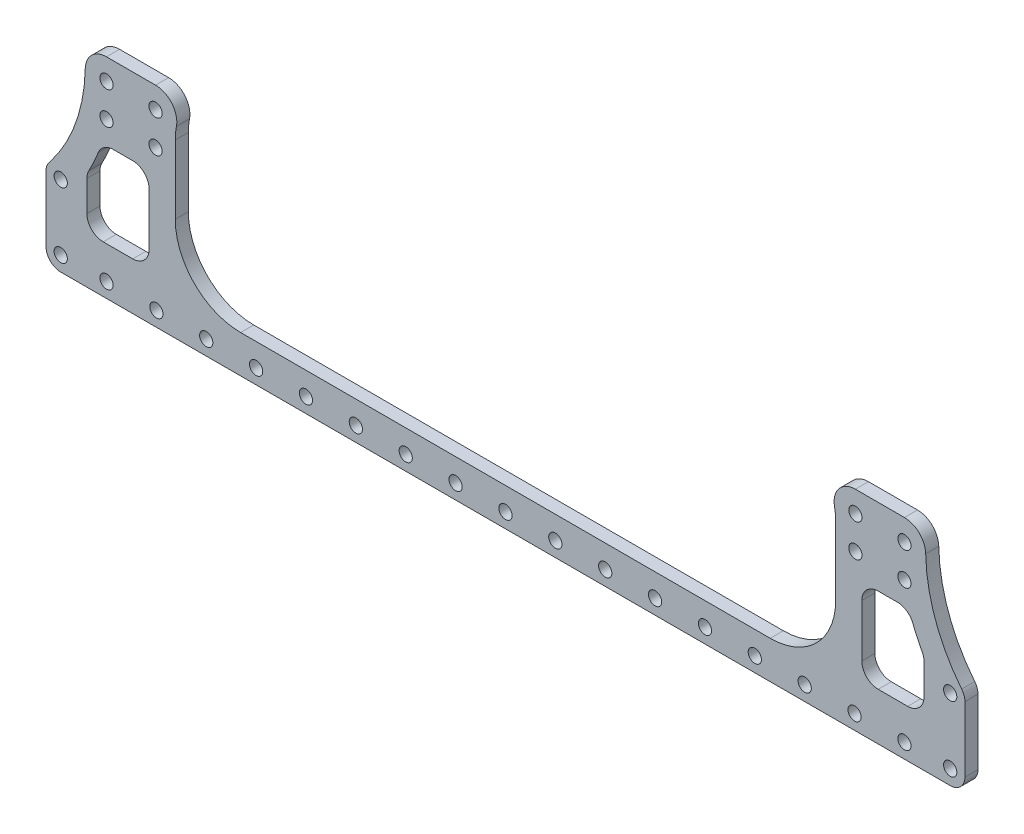
SolidWorks part; units mm, degrees
material "Thornel Mat VMA"
ref_plane "前视基准面" through (0, 0, 0) normal (0, 0, 1) x (1, 0, 0)
ref_plane "上视基准面" through (0, 0, 0) normal (0, 1, 0) x (1, 0, 0)
ref_plane "右视基准面" through (0, 0, 0) normal (1, 0, 0) x (0, 0, -1)
other "Configuration Table"
sketch "草图1" plane through (0, 0, 0) normal (0, 0, 1) x (1, 0, 0)
  line L0 (0, 0) -> (17960.6475, 0) construction
  line L1 (-122, -5) -> (-122, -28) construction
  line L2 (-107, -5) -> (-122, -5) construction
  line L3 (-107, -5) -> (-107, 5) construction
  line L4 (-107, 5) -> (-122, 5) construction
  line L5 (-122, -5) -> (-122, 5) construction
  line L6 (-107, -5) -> (-122, 5) construction
  line L7 (-107, 5) -> (-122, -5) construction
  line L8 (0, 0) -> (0, -50000) construction
  line L9 (107, 5) -> (122, -5) construction
  line L10 (-126, -9) -> (-103, -9) construction
  line L11 (-126, -9) -> (-126, 9) construction
  line L12 (-126, 9) -> (-103, 9) construction
  line L13 (-103, -9) -> (-103, 9) construction
  line L14 (-126, -9) -> (-103, 9) construction
  line L15 (-126, 9) -> (-103, -9) construction
  line L16 (-122, -28) -> (-136, -28) construction
  line L17 (126, -9) -> (103, -9) construction
  line L18 (126, -9) -> (126, 9) construction
  line L19 (126, 9) -> (103, 9) construction
  line L20 (103, -9) -> (103, 9) construction
  line L21 (126, -9) -> (103, 9) construction
  line L22 (126, 9) -> (103, -9) construction
  line L23 (-136, -32.5) -> (136, -32.5)
  line L24 (-80.976, -20) -> (80.976, -20)
  line L25 (122, -28) -> (136, -28) construction
  line L26 (126, 9) -> (103, -9) construction
  line L27 (126, -9) -> (103, 9) construction
  line L28 (103, -9) -> (103, 9) construction
  line L29 (126, 9) -> (103, 9) construction
  line L30 (126, -9) -> (126, 9) construction
  line L31 (126, -9) -> (103, -9) construction
  line L32 (107, 5) -> (122, -5) construction
  line L33 (107, -5) -> (122, 5) construction
  line L34 (122, -5) -> (122, 5) construction
  line L35 (107, 5) -> (122, 5) construction
  line L36 (107, -5) -> (107, 5) construction
  line L37 (107, -5) -> (122, -5) construction
  line L38 (122, -5) -> (122, -28) construction
  line L39 (0, 0) -> (-17960.6475, 0) construction
  line L40 (-122, 11.5) -> (-107, 11.5)
  line L41 (107, 11.5) -> (122, 11.5)
  circle A0 centre (-122, 5) radius 2.025
  circle A1 centre (-107, 5) radius 2.025
  circle A2 centre (-122, -5) radius 2.025
  circle A3 centre (-107, -5) radius 2.025
  circle A4 centre (-122, -28) radius 2.025
  circle A5 centre (122, -5) radius 2.025
  circle A6 centre (107, -5) radius 2.025
  circle A7 centre (107, 5) radius 2.025
  circle A8 centre (122, 5) radius 2.025
  circle A9 centre (-178.4887, 6.1316) radius 50
  circle A10 centre (-122, 5) radius 6.5
  circle A11 centre (-122, -28) radius 6.5 construction
  circle A12 centre (-122, -28) radius 4.5
  circle A13 centre (-136, -28) radius 2.025
  circle A14 centre (-136, -28) radius 4.5
  circle A15 centre (-107, 5) radius 6.5
  circle A17 centre (-80.976, 0) radius 20
  circle A24 centre (122, -28) radius 6.5 construction
  circle A30 centre (80.976, 0) radius 20
  circle A31 centre (107, 5) radius 6.5
  circle A32 centre (136, -28) radius 4.5
  circle A33 centre (136, -28) radius 2.025
  circle A34 centre (122, -28) radius 4.5
  circle A35 centre (122, 5) radius 6.5
  circle A36 centre (178.4887, 6.1316) radius 50
  circle A37 centre (122, -28) radius 2.025
  circle A38 centre (107, -5) radius 2.025
  circle A39 centre (122, -5) radius 2.025
  circle A40 centre (107, 5) radius 2.025
  circle A41 centre (122, 5) radius 2.025
  circle A43 centre (-106.75, -28) radius 2.025
  circle A44 centre (-91.5, -28) radius 2.025
  circle A45 centre (-76.25, -28) radius 2.025
  circle A46 centre (-61, -28) radius 2.025
  circle A47 centre (-45.75, -28) radius 2.025
  circle A48 centre (-30.5, -28) radius 2.025
  circle A49 centre (-15.25, -28) radius 2.025
  circle A50 centre (0, -28) radius 2.025
  circle A52 centre (-106.75, -28) radius 6.5 construction
  circle A53 centre (15.25, -28) radius 2.025 [skipped]
  circle A54 centre (106.75, -28) radius 2.025
  circle A55 centre (91.5, -28) radius 2.025
  circle A56 centre (76.25, -28) radius 2.025
  circle A57 centre (61, -28) radius 2.025
  circle A58 centre (45.75, -28) radius 2.025
  circle A59 centre (30.5, -28) radius 2.025
  circle A60 centre (15.25, -28) radius 2.025
  point P3 (-114.5, 0)
  point P24 (-114.5, 0)
  point P29 (114.5, 0)
  point P91 (0, -20)
  point P92 (0, -32.5)
  dimension "D3" = 4.05
  dimension "D5" = 4.05
  dimension "D8" = 4
  dimension "D9" = 13
  dimension "D10" = 100
  dimension "D11" = 13
  dimension "D12" = 9
  dimension "D14" = 40
  dimension "D1" = 10
  dimension "D2" = 15
  dimension "D4" = 122
  dimension "D6" = 23
  dimension "D7" = 4
  dimension "D13" = 14
  dimension "D15" = 10
extrude "凸台-拉伸1" add sketch "草图1" along normal blind 4
sketch "草图2" plane through (0, 0, 4) normal (0, 0, 1) x (1, 0, 0)
  circle A0 centre (-136, -28) radius 6.5 construction
  dimension "D1" = 13
sketch "草图3" plane through (0, 0, 4) normal (0, 0, 1) x (1, 0, 0)
  line L0 (140.5, -28) -> (140.5, -48)
  line L1 (136, -52.5) -> (-136, -52.5)
  line L2 (-140.5, -48) -> (-140.5, -28)
  line L3 (-136, -32.5) -> (136, -32.5) construction
  line L4 (0, -14.5949) -> (0, 23.9841) construction
  line L5 (-136, -32.5) -> (136, -32.5)
  arc A0 (136, -32.5) -> (139.5082, -25.1818) centre (136, -28) ccw construction
  arc A1 (-139.5082, -25.1818) -> (-136, -32.5) centre (-136, -28) ccw construction
  circle A2 centre (-136, -48) radius 2.025
  circle A3 centre (-136, -28) radius 2.025 construction
  circle A4 centre (-136, -48) radius 4.5
  circle A5 centre (0, -48) radius 2.025
  circle A6 centre (0, -28) radius 2.025 construction
  circle A7 centre (-15.25, -48) radius 2.025
  circle A8 centre (-30.5, -48) radius 2.025
  circle A9 centre (-45.75, -48) radius 2.025
  circle A10 centre (-61, -48) radius 2.025
  circle A11 centre (-76.25, -48) radius 2.025
  circle A12 centre (-91.5, -48) radius 2.025
  circle A13 centre (-106.75, -48) radius 2.025
  circle A14 centre (-122, -48) radius 2.025
  circle A15 centre (-15.25, -28) radius 2.025 construction
  circle A16 centre (-15.25, -28) radius 2.025 construction
  circle A18 centre (122, -48) radius 2.025
  circle A19 centre (106.75, -48) radius 2.025
  circle A20 centre (91.5, -48) radius 2.025
  circle A21 centre (76.25, -48) radius 2.025
  circle A22 centre (61, -48) radius 2.025
  circle A23 centre (45.75, -48) radius 2.025
  circle A24 centre (30.5, -48) radius 2.025
  circle A25 centre (15.25, -48) radius 2.025
  circle A26 centre (136, -48) radius 4.5
  circle A27 centre (136, -48) radius 2.025
  arc A28 (136, -32.5) -> (140.5, -28) centre (136, -28) ccw
  arc A29 (-140.5, -28) -> (-136, -32.5) centre (-136, -28) ccw
  arc M20 (-139.5082, -25.1818) -> (-136, -32.5) centre (-136, -28) ccw
  line M21 (-136, -32.5) -> (136, -32.5)
  arc M22 (136, -32.5) -> (139.5082, -25.1818) centre (136, -28) ccw
  dimension "D1" = 20
  dimension "D2" = 20
  dimension "D3" = 9
extrude "凸台-拉伸2" add sketch "草图3" against normal blind 4 contours L1 A26 L0 L2 A4 A25 A23 A21 A19 A5 A7 A8 A9 A10 A11 A12 A13 A14 A18 A20 A22 A24 M22 M21 M20 | A4 A2 | A26 A27
sketch "草图4" plane through (0, 0, 4) normal (0, 0, 1) x (1, 0, 0)
  line L0 (-100.976, 0) -> (-100.976, -41)
  line L1 (-100.976, -41) -> (100.976, -41)
  line L2 (100.976, -41) -> (100.976, 0)
  line L3 (-80.976, -20) -> (80.976, -20) construction
  line L4 (-80.976, -20) -> (80.976, -20)
  line L5 (0, -9.9748) -> (0, 31.8248) construction
  arc A0 (-100.6167, 3.7736) -> (-80.976, -20) centre (-80.976, 0) ccw construction
  arc A1 (80.976, -20) -> (100.6167, 3.7736) centre (80.976, 0) ccw construction
  arc A2 (-100.976, 0) -> (-80.976, -20) centre (-80.976, 0) ccw
  arc A3 (80.976, -20) -> (100.976, 0) centre (80.976, 0) ccw
  circle A5 centre (76.25, -48) radius 2.025 construction
  circle A6 centre (80.976, -21) radius 20
  circle A7 centre (-80.976, -21) radius 20
  dimension "D1" = 7
extrude "切除-拉伸1" cut sketch "草图4" against normal blind 4 contours A6 A3 L4 | L4 A7 L1 A6 | A7 L4 A2 | L0 A7 A2 | A6 L2 A3
sketch "草图5" plane through (0, 0, 4) normal (0, 0, 1) x (1, 0, 0)
  circle A0 centre (106.75, -28) radius 2.025 construction
  circle A1 centre (122, -28) radius 2.025 construction
  circle A2 centre (-122, -28) radius 2.025 construction
  circle A3 centre (-106.75, -28) radius 2.025 construction
  circle A4 centre (106.75, -28) radius 2.025
  circle A5 centre (122, -28) radius 2.025
  circle A6 centre (-122, -28) radius 2.025
  circle A7 centre (-106.75, -28) radius 2.025
extrude "凸台-拉伸3" add sketch "草图5" against normal blind 4
sketch "草图6" plane through (0, 0, 4) normal (0, 0, 1) x (1, 0, 0)
  line L0 (-108.976, -12) -> (-123.3956, -12)
  line L1 (-108.976, -12) -> (-108.976, -38)
  line L2 (-108.976, -38) -> (-128, -38)
  line L3 (-128, -38) -> (-128, -22.4148)
  line L4 (-100.976, 0) -> (-100.976, -21) construction
  line L5 (0, -16.786) -> (0, 30.4801) construction
  line L6 (128, -38) -> (128, -22.4148)
  line L7 (108.976, -38) -> (128, -38)
  line L8 (108.976, -12) -> (108.976, -38)
  line L9 (108.976, -12) -> (123.3956, -12)
  arc A0 (-128, -22.4148) -> (-123.3956, -12) centre (-178.4887, 6.1316) ccw
  arc A1 (-139.5082, -25.1818) -> (-128.4987, 5.1302) centre (-178.4887, 6.1316) ccw construction
  circle A2 centre (-107, -5) radius 2.025 construction
  circle A3 centre (-106.75, -48) radius 2.025 construction
  circle A4 centre (-136, -28) radius 2.025 construction
  arc A5 (128, -22.4148) -> (123.3956, -12) centre (178.4887, 6.1316) cw
  dimension "D1" = 8
  dimension "D2" = 7
  dimension "D3" = 10
  dimension "D4" = 8
  dimension "D5" = 8
extrude "切除-拉伸2" cut sketch "草图6" against normal blind 4
fillet "圆角1" radius 5 10 edges at (128, -38, 2) (123.3956, -12, 2) (128, -22.4148, 2) (-128, -38, 2) (-128, -22.4148, 2) (-123.3956, -12, 2) (-108.976, -12, 2) (-108.976, -38, 2) (108.976, -38, 2) (108.976, -12, 2)
